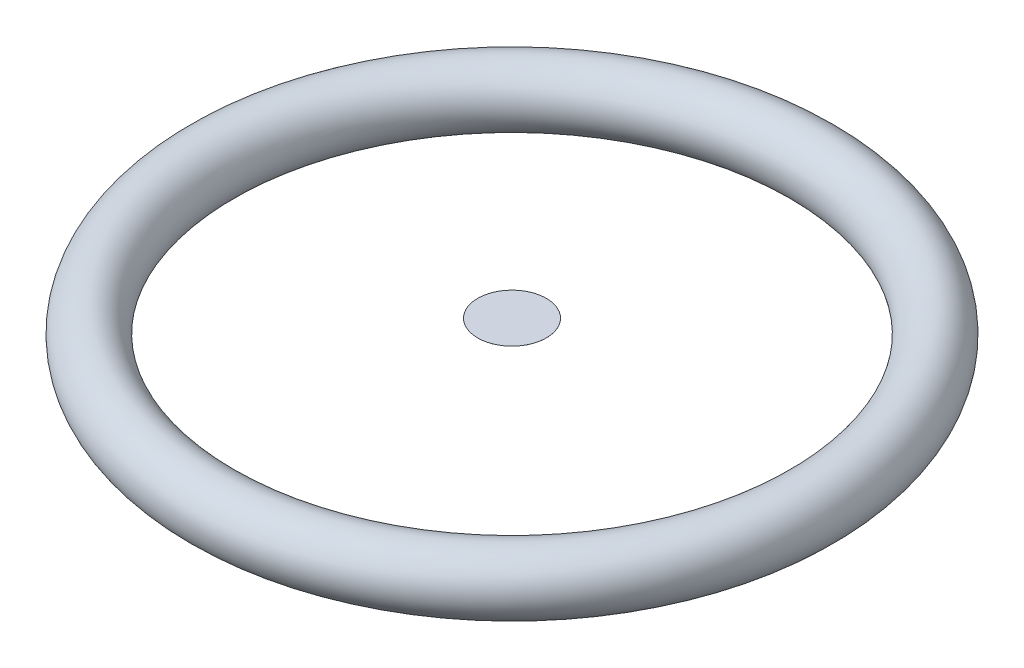
SolidWorks part; units mm, degrees
ref_plane "Front Plane" through (0, 0, 0) normal (0, 0, 1) x (1, 0, 0)
ref_plane "Top Plane" through (0, 0, 0) normal (0, 1, 0) x (1, 0, 0)
ref_plane "Right Plane" through (0, 0, 0) normal (1, 0, 0) x (0, 0, -1)
sketch "Sketch1" plane through (0, 0, 0) normal (0, 0, 1) x (1, 0, 0)
  line L0 (0, 5.15) -> (0, -5.994) construction
  circle A0 centre (17.435, 0) radius 1.765
  dimension "D1" = 3.53
  dimension "D2" = 17.435
revolve "Revolve1" add sketch "Sketch1" angle 360 about L0
ref_plane "Plane1" through (0, 0.8, 0) normal (0, 1, 0) x (1, 0, 0)
sketch "Sketch3" plane through (0, 0.8, 0) normal (0, 1, 0) x (1, 0, 0)
  circle A0 centre (0, 0) radius 2
  dimension "D1" = 4
extrude "Boss-Extrude1" add sketch "Sketch3" against normal blind 0.001 separate body
